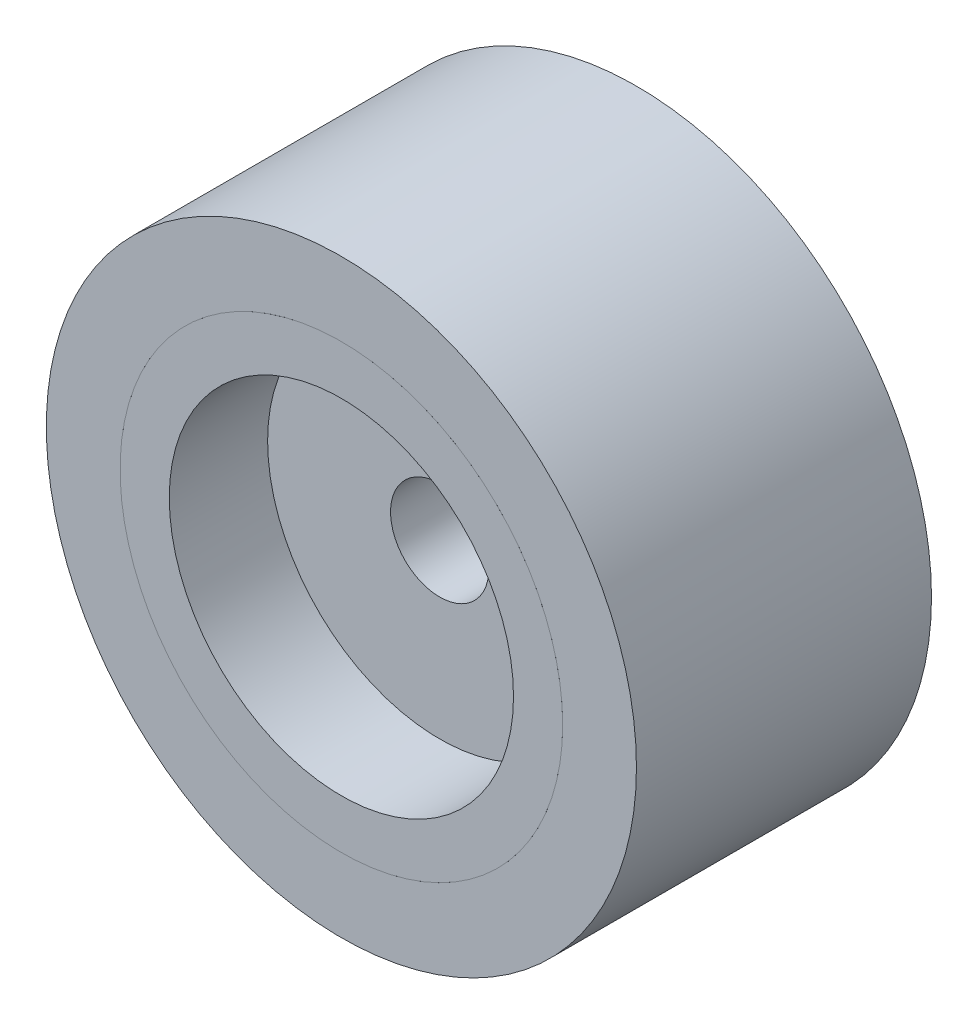
SolidWorks part; units mm, degrees
ref_plane "Front Plane" through (0, 0, 0) normal (0, 0, 1) x (1, 0, 0)
ref_plane "Top Plane" through (0, 0, 0) normal (0, 1, 0) x (1, 0, 0)
ref_plane "Right Plane" through (0, 0, 0) normal (1, 0, 0) x (0, 0, -1)
sketch "Sketch1" plane through (0, 0, 0) normal (1, 0, 0) x (0, 0, -1)
  line L0 (0, 0) -> (141.0669, 0) construction
  line L1 (0, 6) -> (0, 21)
  line L2 (0, 21) -> (-12, 21)
  line L3 (-15, 21) -> (-15, 30) construction
  line L4 (-15, 30) -> (-12, 30) construction
  line L5 (-12, 30) -> (-12, 27) construction
  line L8 (24, 21) -> (12, 21)
  line L9 (12, 21) -> (12, 6)
  line L13 (-12, 36) -> (24, 36) construction
  line L15 (-12, 27) -> (24, 27)
  line L16 (24, 27) -> (24, 30) construction
  line L17 (24, 30) -> (27, 30) construction
  line L18 (27, 30) -> (27, 21) construction
  line L19 (-12, 27) -> (-12, 21)
  line L20 (24, 27) -> (24, 21)
  line L22 (-15, 21) -> (-12, 21) construction
  line L23 (24, 21) -> (27, 21) construction
  line L25 (12, 6) -> (0, 6)
  dimension "D2" = 36
  dimension "D3" = 3
  dimension "D4" = 3
  dimension "D5" = 6
  dimension "D6" = 12
  dimension "D7" = 12
  dimension "D8" = 6
  dimension "D9" = 36
  dimension "D10" = 9
revolve "Revolve1" add sketch "Sketch1" angle 360 about L0
sketch "Sketch2" plane through (0, 0, 0) normal (0, 0, 1) x (1, 0, 0)
  line L0 (0, 15) -> (0, 0) construction
  circle A0 centre (0, 15) radius 4.5
  circle A1 centre (12.9904, 7.5) radius 4.5
  circle A2 centre (12.9904, -7.5) radius 4.5
  circle A3 centre (0, -15) radius 4.5
  circle A4 centre (-12.9904, -7.5) radius 4.5
  circle A5 centre (-12.9904, 7.5) radius 4.5
  point P16 (0, 0)
  dimension "D1" = 9
  dimension "D2" = 15
extrude "Cut-Extrude1" [suppressed] cut sketch "Sketch2" against normal up to surface (12 mm away)
sketch "Sketch3" plane through (0, 0, 0) normal (1, 0, 0) x (0, 0, -1)
  line L0 (23.999, 36) -> (-11.999, 36)
  line L1 (-11.999, 36) -> (-11.999, 27.001)
  line L2 (-11.999, 27.001) -> (23.999, 27.001)
  line L3 (23.999, 27.001) -> (23.999, 36)
  line L4 (24, 27) -> (-12, 27) construction
  line L5 (24, 27) -> (-12, 27) construction
  line L7 (0, 0) -> (11.7609, 0) construction
  line L9 (24, -27) -> (24, 27) construction
  point P11 (24, 0)
  point P12 (0, 0)
  point P13 (11.7609, 0)
  dimension "D1" = 0.001
  dimension "D2" = 0.001
  dimension "D3" = 0.001
  dimension "D4" = 36
revolve "Revolve2" add sketch "Sketch3" angle 360 about L7
